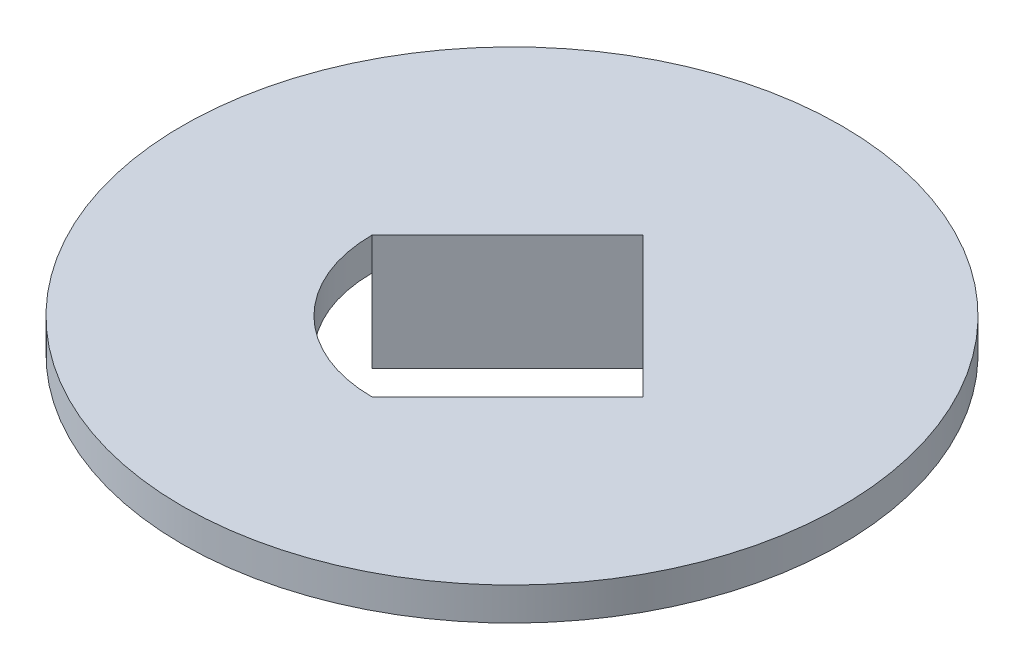
SolidWorks part; units mm, degrees
ref_plane "Front Plane" through (0, 0, 0) normal (0, 0, 1) x (1, 0, 0)
ref_plane "Top Plane" through (0, 0, 0) normal (0, 1, 0) x (1, 0, 0)
ref_plane "Right Plane" through (0, 0, 0) normal (1, 0, 0) x (0, 0, -1)
sketch "Sketch2" plane through (0, 0, 0) normal (0, 1, 0) x (1, 0, 0)
  line L4 (0.0293, -4.0302) -> (-3.9109, -0.09)
  line L5 (-3.9109, -0.09) -> (0.0883, 3.9091)
  line L6 (0.0883, 3.9091) -> (4.0302, -0.0293)
  circle A3 centre (0, 0) radius 10
  arc A7 (0.0293, -4.0302) -> (4.0302, -0.0293) centre (0, 0) cw
extrude "Boss-Extrude1" add sketch "Sketch2" along normal blind 1 contours A3
sketch "Sketch3" plane through (0, 0, 0) normal (0, -1, 0) x (1, 0, 0)
  line L7 (-4.25, 0) -> (-0.1383, -4.1117)
  line L8 (-0.1383, -4.1117) -> (4.1193, 0.1458)
  line L9 (4.1193, 0.1458) -> (0, 4.25)
  arc A0 (0, -4.25) -> (-4.25, 0) centre (0, 0) cw
  arc A1 (0, -4.25) -> (0, 4.25) centre (0, 0) ccw
extrude "Boss-Extrude2" add sketch "Sketch3" along normal blind 2.5
sketch "Sketch4" plane through (0, 0, 0) normal (0, -1, 0) x (1, 0, 0)
  line L4 (-0.1383, -4.1117) -> (4.1193, 0.1458)
  line L5 (4.1193, 0.1458) -> (0, 4.25)
  line L7 (-4.25, 0) -> (-0.1383, -4.1117)
  arc A0 (-4.25, 0) -> (0, 4.25) centre (0, 0) cw
extrude "Cut-Extrude1" cut sketch "Sketch4" against normal blind 2.5
